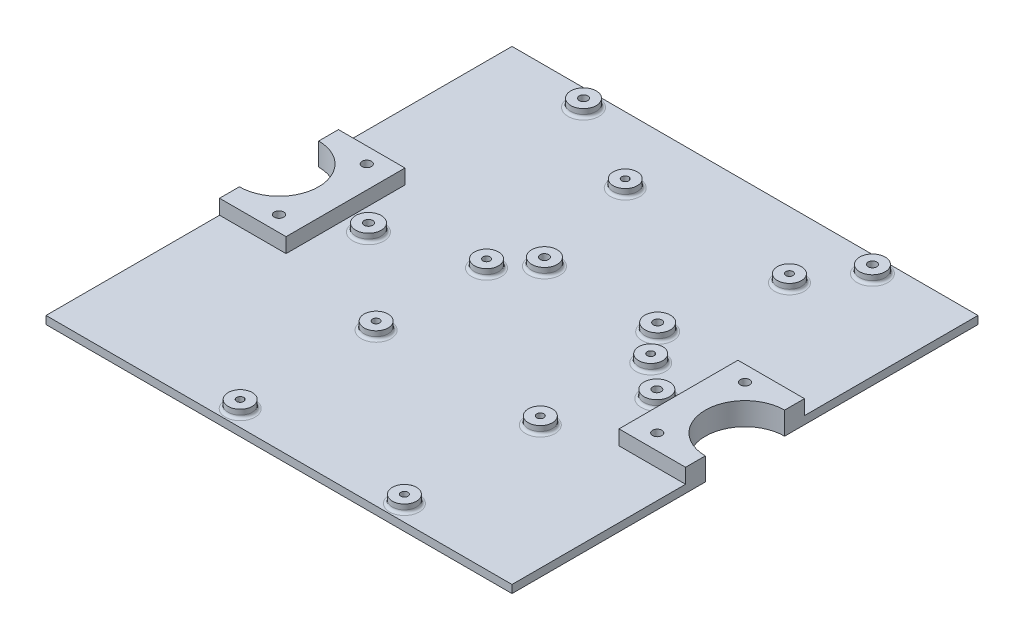
SolidWorks part; units mm, degrees
ref_plane "Front Plane" through (0, 0, 0) normal (0, 0, 1) x (1, 0, 0)
ref_plane "Top Plane" through (0, 0, 0) normal (0, 1, 0) x (1, 0, 0)
ref_plane "Right Plane" through (0, 0, 0) normal (1, 0, 0) x (0, 0, -1)
sketch "Sketch1" plane through (0, 0, 0) normal (0, 1, 0) x (1, 0, 0)
  line L1 (-82.3, -82.3) -> (82.3, -82.3)
  line L2 (-82.3, -82.3) -> (-82.3, 82.3)
  line L3 (-82.3, 82.3) -> (82.3, 82.3)
  line L4 (82.3, -82.3) -> (82.3, 82.3)
  line L5 (-82.3, -82.3) -> (82.3, 82.3) construction
  line L6 (-82.3, 82.3) -> (82.3, -82.3) construction
  point P0 (0, 0)
  dimension "D1" = 164.6
extrude "Boss-Extrude1" add sketch "Sketch1" against normal blind 2.8
sketch "Sketch2" plane through (0, 0, 0) normal (0, 1, 0) x (1, 0, 0)
  line L0 (-82.3, 0) -> (82.3, 0) construction
  line L1 (0, 82.3) -> (0, -82.3) construction
  line L2 (-58.8, -21) -> (-82.3, -21)
  line L3 (-58.8, -21) -> (-58.8, 21)
  line L4 (82.3, -82.3) -> (82.3, 82.3)
  line L5 (82.3, 82.3) -> (-82.3, 82.3)
  line L6 (-82.3, 82.3) -> (-82.3, -82.3)
  line L7 (-82.3, -82.3) -> (82.3, -82.3)
  line L8 (82.3, -82.3) -> (82.3, 82.3)
  line L9 (82.3, 82.3) -> (-82.3, 82.3)
  line L10 (-82.3, 82.3) -> (-82.3, -82.3)
  line L11 (-82.3, -82.3) -> (82.3, -82.3)
  line L12 (-58.8, 21) -> (-82.3, 21)
  line L13 (-82.3, -21) -> (-82.3, 21)
  line L14 (-58.8, -21) -> (-82.3, 21) construction
  line L15 (-58.8, 21) -> (-82.3, -21) construction
  line L16 (58.8, 21) -> (82.3, 21)
  line L17 (82.3, -21) -> (82.3, 21)
  line L18 (58.8, -21) -> (82.3, -21)
  line L19 (58.8, -21) -> (58.8, 21)
  point P6 (-70.55, 0)
  dimension "D2" = 42
  dimension "D3" = 23.5
  dimension "D1" = 0
extrude "Boss-Extrude2" add sketch "Sketch2" along normal blind 5.2 contours L3 L12 L10 L2 | L19 L18 L8 L16
sketch "Sketch3" plane through (0, -2.8, 0) normal (0, -1, 0) x (1, 0, 0)
  line L0 (82.3, 82.3) -> (82.3, -82.3) construction
  line L1 (-82.3, -82.3) -> (-82.3, 82.3) construction
  circle A0 centre (82.3, 0) radius 14
  circle A1 centre (-82.3, 0) radius 14
  dimension "D1" = 28
  dimension "D2" = 28
extrude "Cut-Extrude1" cut sketch "Sketch3" against normal through all both and the other way through all
sketch "Sketch4" plane through (0, -2.8, 0) normal (0, -1, 0) x (1, 0, 0)
  line L0 (0, 0) -> (-82.3, 0) construction
  line L1 (0, 82.3) -> (0, -82.3) construction
  line L2 (-82.3, 82.3) -> (82.3, 82.3) construction
  line L3 (82.3, -82.3) -> (-82.3, -82.3) construction
  line L4 (-82.3, -82.3) -> (-82.3, -14) construction
  circle A0 centre (-66.8, 15.5) radius 1.65
  circle A1 centre (-66.8, -15.5) radius 1.65
  circle A2 centre (66.8, 15.5) radius 1.65
  circle A3 centre (66.8, -15.5) radius 1.65
  dimension "D1" = 3.3
  dimension "D2" = 3.3
  dimension "D3" = 31
  dimension "D4" = 15.5
  dimension "D5" = 15.5
extrude "Cut-Extrude2" cut sketch "Sketch4" against normal through all
sketch "Sketch5" plane through (0, -2.8, 0) normal (0, -1, 0) x (1, 0, 0)
  circle A0 centre (66.8, 15.5) radius 1.65 construction
  circle A1 centre (66.8, -15.5) radius 1.65 construction
  circle A2 centre (-66.8, -15.5) radius 1.65 construction
  circle A3 centre (-66.8, 15.5) radius 1.65 construction
  circle A4 centre (66.8, 15.5) radius 1.65 construction
  circle A5 centre (66.8, -15.5) radius 1.65 construction
  circle A6 centre (-66.8, -15.5) radius 1.65 construction
  circle A7 centre (-66.8, 15.5) radius 1.65 construction
  circle A8 centre (66.8, 15.5) radius 3
  circle A9 centre (66.8, -15.5) radius 3
  circle A10 centre (-66.8, -15.5) radius 3
  circle A11 centre (-66.8, 15.5) radius 3
  dimension "D1" = 6
extrude "Cut-Extrude3" cut sketch "Sketch5" against normal blind 3.2
sketch "Sketch6" plane through (0, 0, 0) normal (0, 1, 0) x (1, 0, 0)
  circle A28 centre (-19.5, -76.5) radius 1.25
  circle A29 centre (-19.5, -28.5) radius 1.25
  circle A30 centre (38.5, -28.5) radius 1.25
  circle A31 centre (38.5, -76.5) radius 1.25
  circle A32 centre (-9.321, 20.778) radius 1.5
  circle A33 centre (30.679, 20.778) radius 1.5
  circle A34 centre (-50.8698, 0.1725) radius 1.5
  circle A35 centre (-19, 10) radius 1.25
  circle A36 centre (39, 10) radius 1.25
  circle A37 centre (50.9842, 0.1725) radius 1.5
  circle A38 centre (50.8445, 76.4741) radius 1.5
  circle A39 centre (-51.0095, 76.2709) radius 1.5
  circle A40 centre (-19, 59) radius 1.25
  circle A41 centre (39, 59) radius 1.25
  point P22 (0, 0)
  point P23 (0, 0)
  dimension "D1" = 2.5
  dimension "D2" = 2.5
  dimension "D3" = 2.5
  dimension "D4" = 2.5
  dimension "D5" = 3
  dimension "D6" = 3
  dimension "D7" = 3
  dimension "D8" = 3
  dimension "D9" = 3
  dimension "D10" = 3
  dimension "D11" = 2.5
  dimension "D12" = 2.5
  dimension "D13" = 2.5
  dimension "D14" = 2.5
extrude "Cut-Extrude4" cut sketch "Sketch6" against normal through all
sketch "Sketch7" plane through (0, 0, 0) normal (0, 1, 0) x (1, 0, 0)
  circle A0 centre (38.5, -76.5) radius 1.25 construction
  circle A1 centre (-19.5, -76.5) radius 1.25 construction
  circle A2 centre (-19.5, -28.5) radius 1.25 construction
  circle A3 centre (38.5, -28.5) radius 1.25 construction
  circle A4 centre (50.9842, 0.1725) radius 1.5 construction
  circle A5 centre (39, 10) radius 1.25 construction
  circle A6 centre (30.679, 20.778) radius 1.5 construction
  circle A7 centre (-9.321, 20.778) radius 1.5 construction
  circle A8 centre (-19, 10) radius 1.25 construction
  circle A9 centre (-50.8698, 0.1725) radius 1.5 construction
  circle A10 centre (50.8445, 76.4741) radius 1.5 construction
  circle A11 centre (39, 59) radius 1.25 construction
  circle A12 centre (-19, 59) radius 1.25 construction
  circle A13 centre (-51.0095, 76.2709) radius 1.5 construction
  circle A14 centre (38.5, -76.5) radius 1.25
  circle A15 centre (-19.5, -76.5) radius 1.25
  circle A16 centre (-19.5, -28.5) radius 1.25
  circle A17 centre (38.5, -28.5) radius 1.25
  circle A18 centre (50.9842, 0.1725) radius 1.5
  circle A19 centre (39, 10) radius 1.25
  circle A20 centre (30.679, 20.778) radius 1.5
  circle A21 centre (-9.321, 20.778) radius 1.5
  circle A22 centre (-19, 10) radius 1.25
  circle A23 centre (-50.8698, 0.1725) radius 1.5
  circle A24 centre (50.8445, 76.4741) radius 1.5
  circle A25 centre (39, 59) radius 1.25
  circle A26 centre (-19, 59) radius 1.25
  circle A27 centre (-51.0095, 76.2709) radius 1.5
  circle A28 centre (38.5, -76.5) radius 4.25
  circle A29 centre (-19.5, -76.5) radius 4.25
  circle A30 centre (-19.5, -28.5) radius 4.25
  circle A31 centre (38.5, -28.5) radius 4.25
  circle A32 centre (50.9842, 0.1725) radius 4.5
  circle A33 centre (39, 10) radius 4.25
  circle A34 centre (30.679, 20.778) radius 4.5
  circle A35 centre (-9.321, 20.778) radius 4.5
  circle A36 centre (-19, 10) radius 4.25
  circle A37 centre (-50.8698, 0.1725) radius 4.5
  circle A38 centre (50.8445, 76.4741) radius 4.5
  circle A39 centre (39, 59) radius 4.25
  circle A40 centre (-19, 59) radius 4.25
  circle A41 centre (-51.0095, 76.2709) radius 4.5
  dimension "D1" = 3
extrude "Boss-Extrude3" add sketch "Sketch7" along normal blind 2.8
fillet "Fillet1" radius 1 14 edges at (-51.0095, 0, -80.7709) (-19, 0, -63.25) (50.8445, 0, -80.9741) (39, 0, -63.25) (38.5, 0, 72.25) (-19.5, 0, 72.25) (-19.5, 0, 24.25) (38.5, 0, 24.25) (50.9842, 0, -4.6725) (39, 0, -14.25) (30.679, 0, -25.278) (-9.321, 0, -25.278) (-50.8698, 0, -4.6725) (-19, 0, -14.25)
